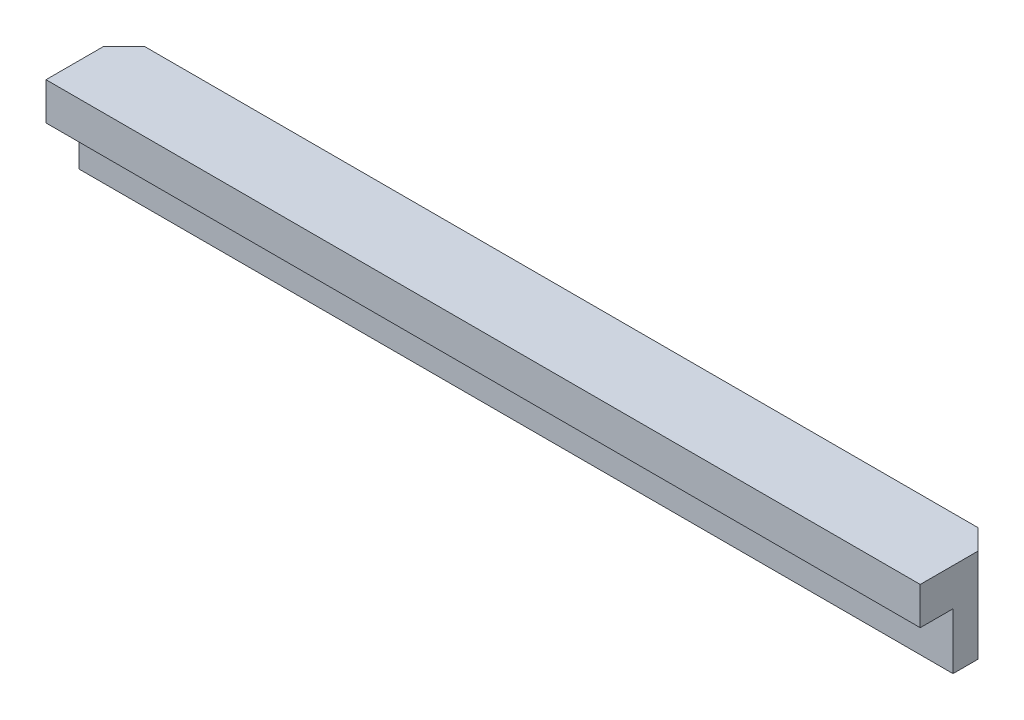
SolidWorks part; units mm, degrees
material "Brass"
ref_plane "Front Plane" through (0, 0, 0) normal (0, 0, 1) x (1, 0, 0)
ref_plane "Top Plane" through (0, 0, 0) normal (0, 1, 0) x (1, 0, 0)
ref_plane "Right Plane" through (0, 0, 0) normal (1, 0, 0) x (0, 0, -1)
sketch "Sketch1" plane through (0, 0, 0) normal (0, 1, 0) x (1, 0, 0)
  line L1 (-140, 12.5) -> (140, 12.5)
  line L2 (-140, 12.5) -> (-140, -12.5)
  line L3 (-140, -12.5) -> (140, -12.5)
  line L4 (140, 12.5) -> (140, -12.5)
  line L6 (-140, 0) -> (140, 0) construction
  point P0 (0, 0)
extrude "Boss-Extrude1" add sketch "Sketch1" along normal blind 30
sketch "Sketch2" plane through (140, 0, 0) normal (1, 0, 0) x (0, 0, -1)
  line L1 (-12.5, 0) -> (-2, 0)
  line L2 (-12.5, 0) -> (-12.5, 18)
  line L3 (-12.5, 18) -> (-2, 18)
  line L4 (-2, 0) -> (-2, 18)
extrude "Cut-Extrude1" cut sketch "Sketch2" against normal blind 300
chamfer "Chamfer1" distance 6.5 angle 45 2 edges at (-140, 15, -12.5) (140, 15, -12.5)
